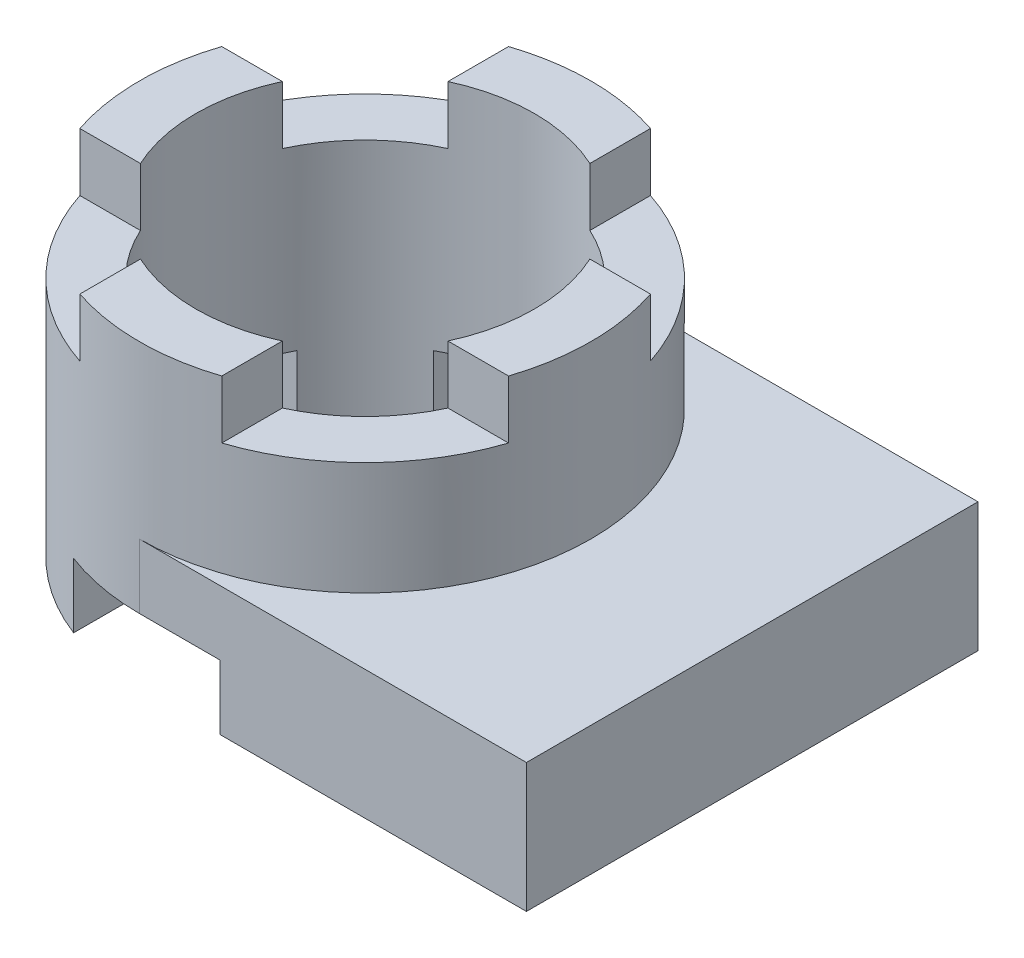
SolidWorks part; units mm, degrees
ref_plane "前视基准面" through (0, 0, 0) normal (0, 0, 1) x (1, 0, 0)
ref_plane "上视基准面" through (0, 0, 0) normal (0, 1, 0) x (1, 0, 0)
ref_plane "右视基准面" through (0, 0, 0) normal (1, 0, 0) x (0, 0, -1)
other "Configuration Table"
sketch "草图1" plane through (0, 0, 0) normal (0, 1, 0) x (1, 0, 0)
  line L1 (0, 7) -> (12, 7)
  line L3 (0, -7) -> (12, -7)
  line L4 (12, 7) -> (12, -7)
  circle A0 centre (0, 0) radius 5.25
  circle A1 centre (0, 0) radius 7
  dimension "D1" = 10.5
  dimension "D2" = 14
  dimension "D3" = 12
extrude "凸台-拉伸3" add sketch "草图1" along normal blind 4 contours A1 L3 L4 L1 | A1 A0
sketch "草图2" plane through (0, 4, 0) normal (0, 1, 0) x (1, 0, 0)
  circle A0 centre (0, 0) radius 7
  arc A1 (0, 7) -> (0, -7) centre (0, 0) ccw construction
  circle A2 centre (0, 0) radius 5.25
  circle A3 centre (0, 0) radius 5.25 construction
extrude "凸台-拉伸4" add sketch "草图2" along normal blind 3.5 contours A0 | A2
sketch "草图3" plane through (0, 0, 0) normal (0, -1, 0) x (1, 0, 0)
  line L0 (0, 0) -> (0, 5.15) construction
  line L1 (0, 0) -> (-6, 0) construction
  line L2 (-2.5, -8.5) -> (2.5, -8.5)
  line L4 (-6, 2.5) -> (-6, -2.5)
  line L5 (-6, -2.5) -> (-2.5, -2.5)
  line L6 (6, 2.5) -> (6, -2.5)
  line L8 (-2.5, 2.5) -> (-2.5, 8.5)
  line L9 (-2.5, 8.5) -> (2.5, 8.5)
  line L10 (2.5, 2.5) -> (2.5, 8.5)
  line L15 (2.5, -2.5) -> (2.5, -8.5)
  line L17 (-2.5, -2.5) -> (-2.5, -8.5)
  line L19 (2.5, -2.5) -> (6, -2.5)
  line L20 (-6, 2.5) -> (-2.5, 2.5)
  line L21 (6, 2.5) -> (2.5, 2.5)
  circle A0 centre (0, 0) radius 7
  arc A1 (0, 7) -> (0, -7) centre (0, 0) ccw construction
  dimension "D1" = 6
  dimension "D2" = 6
  dimension "D4" = 2.5
  dimension "D5" = 2.5
  dimension "D6" = 2.5
  dimension "D7" = 6
extrude "切除-拉伸1" cut sketch "草图3" against normal blind 2 contours L21 L10 L9 L8 L20 L4 L5 L17 L2 L15 L19 L6
sketch "草图4" plane through (0, 7.5, 0) normal (0, 1, 0) x (1, 0, 0)
  line L0 (2.2, 2.2) -> (8.2, 2.2)
  line L5 (8.2, 2.2) -> (8.2, -2.2)
  line L6 (8.2, -2.2) -> (2.2, -2.2)
  line L7 (2.2, -2.2) -> (2.2, -8.2)
  line L8 (2.2, -8.2) -> (-2.2, -8.2)
  line L9 (-2.2, -8.2) -> (-2.2, -2.2)
  line L10 (-2.2, -2.2) -> (-8.2, -2.2)
  line L11 (-8.2, -2.2) -> (-8.2, 2.2)
  line L12 (-8.2, 2.2) -> (-2.2, 2.2)
  line L13 (-2.2, 2.2) -> (-2.2, 8.2)
  line L14 (-2.2, 8.2) -> (2.2, 8.2)
  line L15 (2.2, 8.2) -> (2.2, 2.2)
  line L16 (0, 0) -> (6, 0) construction
  line L18 (0, -6) -> (0, 0) construction
  circle M17 centre (0, 0) radius 7
  circle M18 centre (0, 0) radius 5.25
  dimension "D1" = 2.2
  dimension "D2" = 2.2
  dimension "D3" = 2.2
  dimension "D4" = 2.2
  dimension "D5" = 2.2
  dimension "D6" = 2.2
  dimension "D7" = 2.2
  dimension "D8" = 2.2
  dimension "D9" = 6
  dimension "D10" = 6
  dimension "D11" = 6
  dimension "D12" = 6
extrude "凸台-拉伸5" add sketch "草图4" along normal blind 1.8 contours L12 L10 M17 M18 | L15 L13 M17 M18 | L6 L0 M17 M18 | L9 L7 M17 M18
